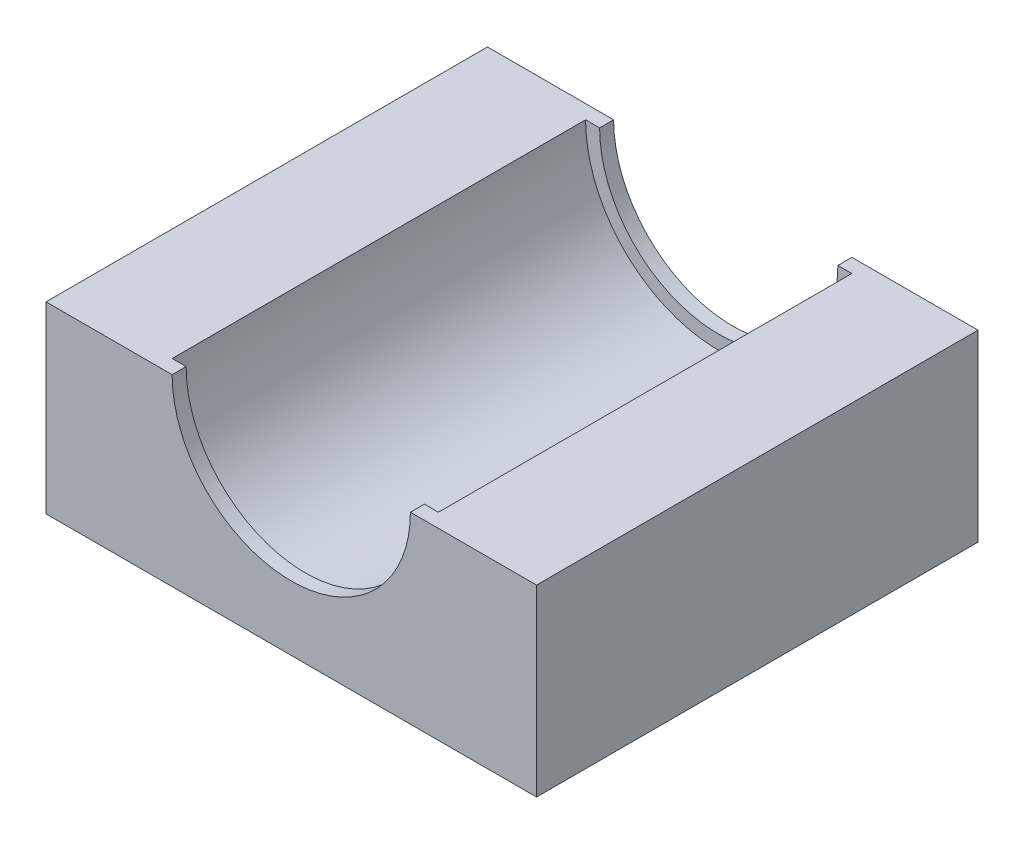
SolidWorks part; units mm, degrees
ref_plane "Front Plane" through (0, 0, 0) normal (0, 0, 1) x (1, 0, 0)
ref_plane "Top Plane" through (0, 0, 0) normal (0, 1, 0) x (1, 0, 0)
ref_plane "Right Plane" through (0, 0, 0) normal (1, 0, 0) x (0, 0, -1)
sketch "Sketch1" plane through (0, 0, 0) normal (0, 0, 1) x (1, 0, 0)
  line L0 (0, 0) -> (70, 0)
  line L1 (70, 0) -> (70, 26.2)
  line L2 (70, 26.2) -> (54, 26.2)
  line L3 (0, 26.2) -> (0, 0)
  line L4 (16, 26.2) -> (0, 26.2)
  arc A0 (16, 26.2) -> (54, 26.2) centre (35, 26.2) ccw
  point P6 (35.0887, 26.2)
  point P9 (35, 0)
  dimension "D1" = 19
  dimension "D2" = 26.2
  dimension "D3" = 70
extrude "Boss-Extrude1" add sketch "Sketch1" along normal blind 63 contours A0 L2 L1 L0 L3 L4
sketch "Sketch2" plane through (0, 0, 63) normal (0, 0, 1) x (1, 0, 0)
  line L0 (18, 26.2) -> (16, 26.2)
  line L1 (52, 26.2) -> (54, 26.2)
  arc A1 (16, 26.2) -> (54, 26.2) centre (35, 26.2) ccw construction
  arc A2 (18, 26.2) -> (52, 26.2) centre (35, 26.2) ccw
  arc A3 (18, 26.2) -> (52, 26.2) centre (35, 26.2) ccw
  arc A4 (16, 26.2) -> (54, 26.2) centre (35, 26.2) ccw
  point P0 (50.8538, 32.7813)
  dimension "D1" = 2
extrude "Boss-Extrude2" add sketch "Sketch2" against normal blind 2
ref_plane "Plane1" through (0, 0, 31.5) normal (0, 0, -1) x (-1, 0, 0)
mirror "Mirror1" about plane through (0, 0, 31.5) normal (0, 0, -1) of "Boss-Extrude2"
